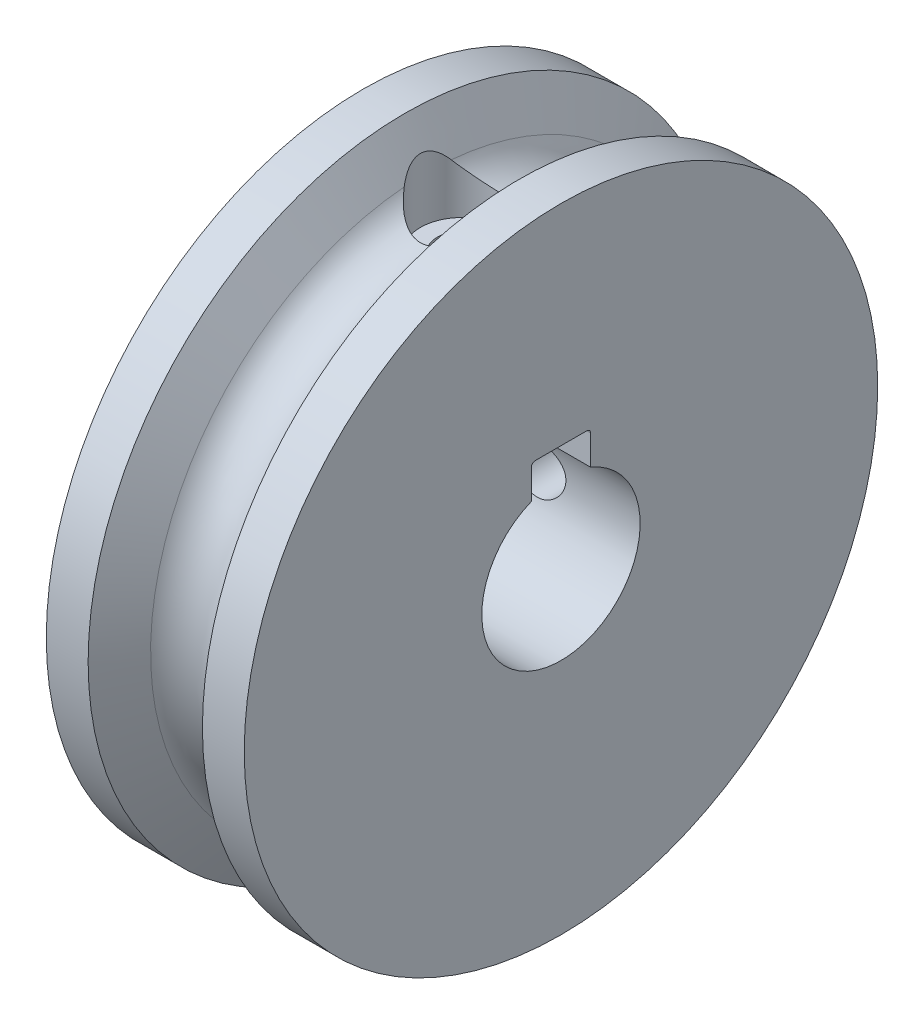
SolidWorks part; units mm, degrees
material "相當於S45C"
ref_plane "Front Plane" through (0, 0, 0) normal (0, 0, 1) x (1, 0, 0)
ref_plane "Top Plane" through (0, 0, 0) normal (0, 1, 0) x (1, 0, 0)
ref_plane "Right Plane" through (0, 0, 0) normal (1, 0, 0) x (0, 0, -1)
sketch "Sketch1" plane through (0, 0, 0) normal (0, 0, 1) x (1, 0, 0)
  line L0 (0, 4) -> (0, 16)
  line L5 (0, 16) -> (10, 16)
  line L6 (10, 16) -> (10, 4)
  line L7 (0, 0) -> (10, 0) construction
  line L8 (10, 4) -> (0, 4)
  line L9 (5, 16) -> (5, 0) construction
  dimension "T" = 10
  dimension "N" = 8
  dimension "D1." = 32
revolve "Revolve1" add sketch "Sketch1" angle 360 about L7
ref_plane "Plane1" through (0, 15, 0) normal (0, 1, 0) x (1, 0, 0)
sketch "Sketch2" plane through (0, 0, 0) normal (0, 0, 1) x (1, 0, 0)
  line L0 (5, 0) -> (5, 16) construction
  line L1 (10, -16) -> (10, 16) construction
  line L2 (0, 0) -> (10, 0) construction
  line L5 (0, 16) -> (0, -16) construction
  line L6 (5, 16) -> (7.1, 16)
  line L7 (5, 16) -> (5, 11.4)
  line L8 (5, 11.4) -> (7.1, 11.4)
  line L9 (7.1, 16) -> (7.1, 11.4)
  line L10 (0, 16) -> (10, 16) construction
  dimension "MSM_1" = 4.2
  dimension "D1" = 11.4
revolve "Cut-Revolve1" cut sketch "Sketch2" angle 360 about L9
hole_wizard "Tapped Hole1" positions "Sketch4" profile "Sketch3" tap size "M3x0.5" standard "JIS"
sketch "Sketch4" plane through (0, 15, 0) normal (0, 1, 0) x (1, 0, 0)
  line L0 (0, 0) -> (10, 0) construction
  line L1 (0, 16) -> (0, -16) construction
  line L3 (10, -16) -> (10, 16) construction
  point P0 (5, 0)
sketch "Sketch3" plane through (5, 15, 0) normal (1, 0, 0) x (0, 0, 1)
  line L0 (0, 0) -> (0, 31)
  line L1 (0, 31) -> (1.25, 31)
  line L2 (1.25, 31) -> (1.25, 0)
  line L5 (1.25, 0) -> (0, 0)
  line L11 (0, 0) -> (0, 31) construction
  dimension "Thru Tap Drill Dia." = 2.5
  dimension "Thru Tap Drill Depth" = 31
cosmetic thread "Hole Thread1" parameters "D1"=3
pattern_circular "CirPattern1" count 2 every 90 about axis through (0, 0, 0) along (-1, 0, 0) of "Cut-Revolve1", "Tapped Hole1"
pattern_circular "CirPattern2" [suppressed] count 2 every 90
sketch "Sketch5" plane through (0, 0, 0) normal (1, 0, 0) x (0, 0, -1)
  line L0 (0, 0) -> (0, 4) construction
  line L1 (-1.5, 0) -> (1.5, 0)
  line L2 (-1.5, 0) -> (-1.5, 5.2)
  line L3 (-1.3, 5.4) -> (1.3, 5.4)
  line L4 (1.5, 0) -> (1.5, 5.2)
  arc A1 (1.3, 5.4) -> (1.5, 5.2) centre (1.3, 5.2) cw
  arc A2 (-1.5, 5.2) -> (-1.3, 5.4) centre (-1.3, 5.2) cw
  circle A3 centre (0, 0) radius 4 construction
  dimension "D1" = 0.2
  dimension "B_s" = 3
  dimension "T_s" = 1.4
extrude "Cut-Extrude1" cut sketch "Sketch5" along normal through all
sketch "Sketch6" [suppressed] plane through (0, 0, 0) normal (0, 0, 1) x (1, 0, 0)
  line L0 (0, 0) -> (10, 0) construction
  line L1 (10, -23.5) -> (10, 23.5) construction
  line L2 (5, 0) -> (5, 23.5) construction
  line L4 (2.9358, 23.5) -> (3.9713, 21)
  line L5 (3.9713, 21) -> (6.0287, 21)
  line L6 (6.0287, 21) -> (7.0642, 23.5)
  line L7 (7.0642, 23.5) -> (2.9358, 23.5)
  line L8 (3.35, 22.5) -> (6.65, 22.5) construction
  line L11 (0, 23.5) -> (10, 23.5) construction
  dimension "D1" = 45
  dimension "W" = 4.4
  dimension "D2." = 26
  dimension "D3" = 1
  dimension "H_s" = 1.5
  dimension "P.D." = 30
revolve "Cut-Revolve2" [suppressed] cut sketch "Sketch6" angle 360 about L0
sketch "Sketch7" plane through (0, 0, 0) normal (0, 0, 1) x (1, 0, 0)
  line L0 (0, 0) -> (10, 0) construction
  line L1 (10, -16) -> (10, 16) construction
  line L2 (5, 0) -> (5, 16) construction
  line L3 (0, 16) -> (10, 16) construction
  line L4 (2.1132, 16) -> (3.2679, 14)
  line L5 (7.8868, 16) -> (6.7321, 14)
  line L6 (2.1132, 16) -> (7.8868, 16)
  line L7 (0, 15) -> (10, 15) construction
  line L8 (10, 16) -> (10, 4) construction
  line L9 (0, 4) -> (0, 16) construction
  arc A0 (3.2679, 14) -> (6.7321, 14) centre (5, 15) ccw
  point P10 (5, 13)
  dimension "D1" = 60
  dimension "R" = 2
  dimension "D2." = 26
  dimension "H_s" = 2
  dimension "P.D." = 30
revolve "Cut-Revolve3" cut sketch "Sketch7" angle 360 about L7
sketch "Sketch8" [suppressed] plane through (0, 0, 0) normal (0, 0, 1) x (1, 0, 0)
  line L0 (0, 0) -> (10, 0) construction
  line L1 (10, -23.5) -> (10, 23.5) construction
  line L2 (0, 5) -> (0, 23.5) construction
  line L3 (0, 23.5) -> (10, 23.5) construction
  line L4 (0, 22.5) -> (10, 22.5) construction
  line L7 (0, 23.5) -> (10, 23.5)
  line L8 (0, 23.5) -> (0, 23.1)
  line L9 (0, 23.1) -> (10, 23.1)
  line L10 (10, 23.5) -> (10, 23.1)
  dimension "DC" = 46.2
  dimension "MSM_1" = 0.6
  dimension "P.D." = 30
revolve "Cut-Revolve4" [suppressed] cut sketch "Sketch8" angle 360 about L0
equation "\"D1@Sketch2\" = ( \"N@Sketch1\" / 2 ) + \"T_s@Sketch5\" + 6"
equation "\"Plane dim\"= \"P.D.\" * 0.5"
equation "\"Belt Radius\"= 1.5"
equation "\"Cut-Revolve1\"= if ( ( \"D1.@Sketch1\" - \"N@Sketch1\" ) / 2 - \"T_s@Sketch5\" > = 6 , \"unsuppressed\" , \"suppressed\" )"
equation "\"CirPattern1\" = if ( ( \"D1.@Sketch1\" - \"N@Sketch1\" ) / 2 - \"T_s@Sketch5\" > = 6 , \"unsuppressed\" , \"suppressed\" )"
equation "\"CirPattern2\" = if ( ( \"D1.@Sketch1\" - \"N@Sketch1\" ) / 2 - \"T_s@Sketch5\" > 6 , \"suppressed\" , \"unsuppressed\" )"
